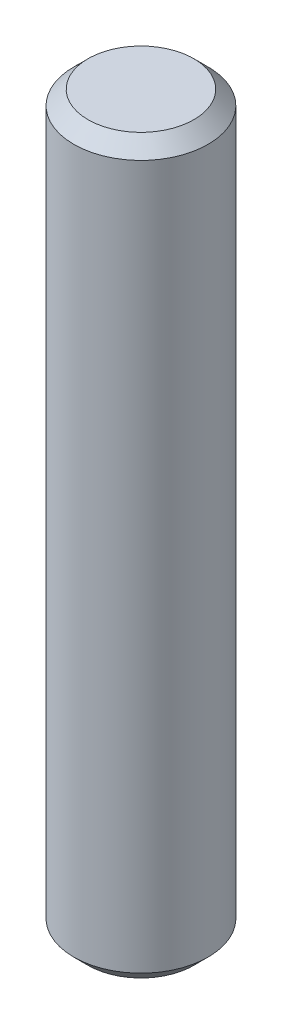
SolidWorks part; units mm, degrees
ref_plane "Front Plane" through (0, 0, 0) normal (0, 0, 1) x (1, 0, 0)
ref_plane "Top Plane" through (0, 0, 0) normal (0, 1, 0) x (1, 0, 0)
ref_plane "Right Plane" through (0, 0, 0) normal (1, 0, 0) x (0, 0, -1)
sketch "Sketch1" plane through (0, 0, 0) normal (0, 1, 0) x (1, 0, 0)
  circle A0 centre (0, 0) radius 1.65
  dimension "D1" = 3.3
extrude "Boss-Extrude1" add sketch "Sketch1" along normal blind 18
chamfer "Chamfer1" distance 0.35 angle 45 2 edges at (0, 0, 1.65) (0, 18, 1.65)
